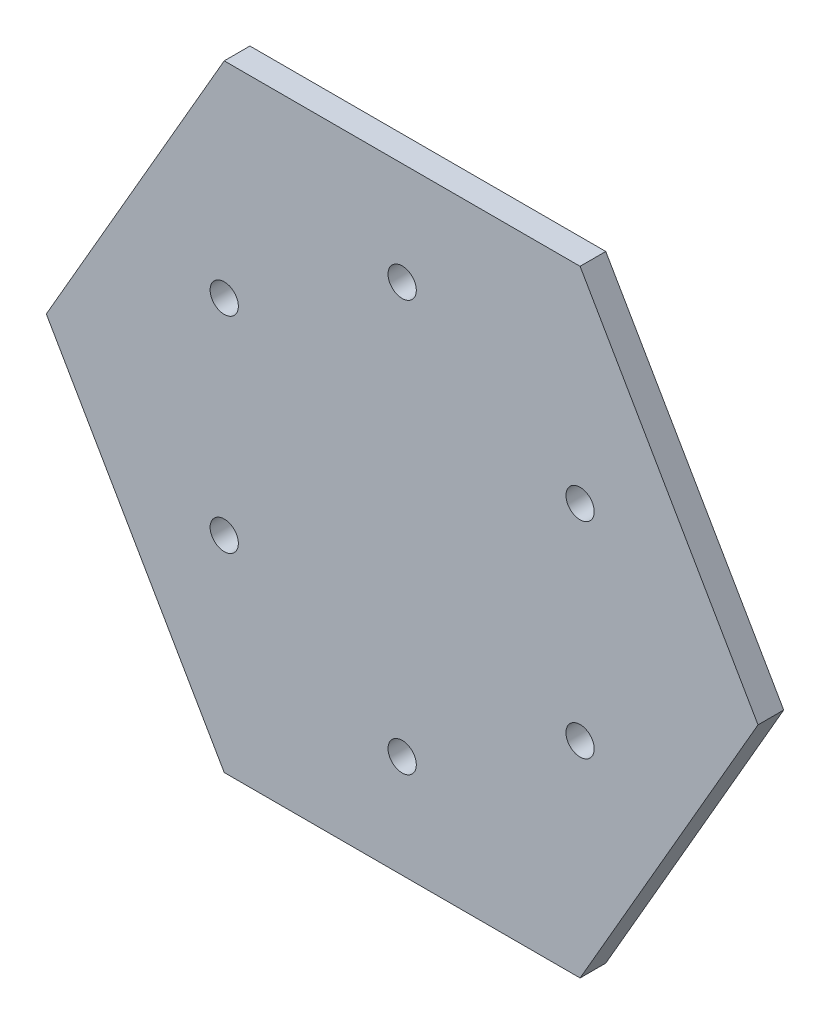
SolidWorks part; units mm, degrees
ref_plane "Front Plane" through (0, 0, 0) normal (0, 0, 1) x (1, 0, 0)
ref_plane "Top Plane" through (0, 0, 0) normal (0, 1, 0) x (1, 0, 0)
ref_plane "Right Plane" through (0, 0, 0) normal (1, 0, 0) x (0, 0, -1)
sketch "Sketch1" plane through (0, 0, 0) normal (0, 0, 1) x (1, 0, 0)
  line L0 (0, 0) -> (-131.9823, 228.6)
  line L1 (-131.9823, 228.6) -> (131.9823, 228.6)
  line L2 (131.9823, 228.6) -> (0, 0)
  line L3 (0, 0) -> (131.9823, 228.6)
  line L4 (131.9823, 228.6) -> (263.9645, 0)
  line L5 (263.9645, 0) -> (0, 0)
  line L6 (0, 0) -> (263.9645, 0)
  line L7 (263.9645, 0) -> (131.9823, -228.6)
  line L8 (131.9823, -228.6) -> (0, 0)
  line L9 (0, 0) -> (131.9823, -228.6)
  line L10 (131.9823, -228.6) -> (-131.9823, -228.6)
  line L11 (-131.9823, -228.6) -> (0, 0)
  line L12 (0, 0) -> (-131.9823, -228.6)
  line L13 (-131.9823, -228.6) -> (-263.9645, 0)
  line L14 (-263.9645, 0) -> (0, 0)
  line L15 (0, 0) -> (-263.9645, 0)
  line L16 (-263.9645, 0) -> (-131.9823, 228.6)
  line L17 (-131.9823, 228.6) -> (0, 0)
  circle A0 centre (0, 152.4) radius 10.4775
  circle A1 centre (131.9823, 76.2) radius 10.4775
  circle A2 centre (131.9823, -76.2) radius 10.4775
  circle A3 centre (0, -152.4) radius 10.4775
  circle A4 centre (-131.9823, -76.2) radius 10.4775
  circle A5 centre (-131.9823, 76.2) radius 10.4775
  point P29 (0, 0)
  dimension "D2" = 20.955
  dimension "D1" = 60
  dimension "D3" = 228.6
  dimension "D4" = 152.4
  dimension "D5" = 6
extrude "Boss-Extrude1" add sketch "Sketch1" along normal blind 19.05 contours L16 L14 L0 A5 | L2 L1 L0 A0 | L5 L4 L2 A1 | L8 L7 L5 A2 | L11 L10 L8 A3 | L14 L13 L11 A4
